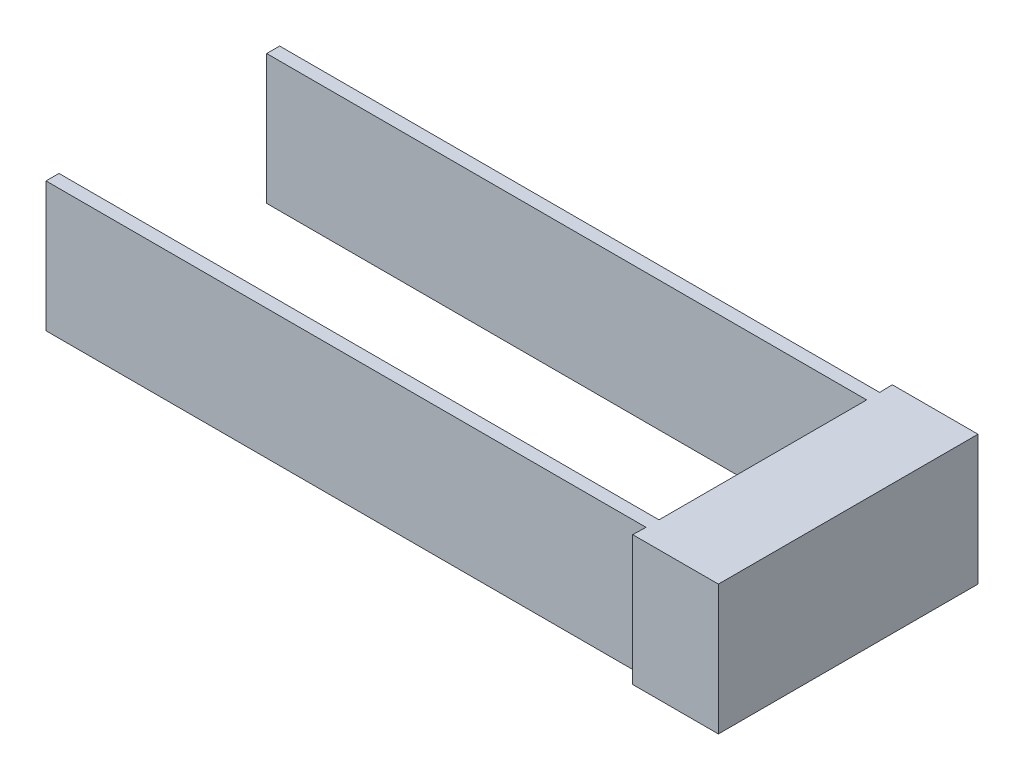
SolidWorks part; units mm, degrees
ref_plane "Front Plane" through (0, 0, 0) normal (0, 0, 1) x (1, 0, 0)
ref_plane "Top Plane" through (0, 0, 0) normal (0, 1, 0) x (1, 0, 0)
ref_plane "Right Plane" through (0, 0, 0) normal (1, 0, 0) x (0, 0, -1)
sketch "Sketch1" plane through (0, 0, 0) normal (0, 1, 0) x (1, 0, 0)
  line L0 (49.5584, 0) -> (49.5, -2.5)
  line L1 (-66, 0) -> (49.5584, 0)
  line L2 (-66, 0) -> (-66, 2.5)
  line L3 (-66, 2.5) -> (49.5584, 2.5)
  line L5 (49.5584, 42.5) -> (-66, 42.5)
  line L7 (49.5584, 45) -> (-66, 45)
  line L8 (-66, 42.5) -> (-66, 45)
  line L10 (49.5584, 2.5) -> (49.5584, 42.5)
  line L12 (66, 0) -> (66, 45)
  line L14 (49.5, -2.5) -> (66, -2.5)
  line L15 (66, -2.5) -> (66, 0)
  line L16 (66, 45) -> (66, 47.5)
  line L17 (66, 47.5) -> (49.5, 47.5)
  line L19 (49.5, 47.5) -> (49.5584, 45)
  dimension "D1" = 2.5
extrude "Boss-Extrude1" add sketch "Sketch1" along normal blind 25
